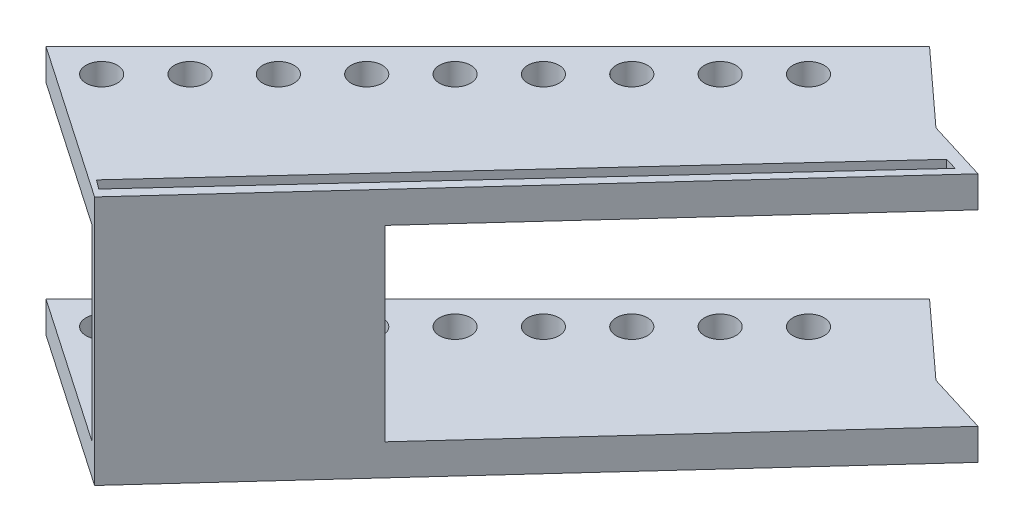
SolidWorks part; units mm, degrees
material "Chrome Stainless Steel"
ref_plane "Front Plane" through (0, 0, 0) normal (0, 0, 1) x (1, 0, 0)
ref_plane "Top Plane" through (0, 0, 0) normal (0, 1, 0) x (1, 0, 0)
ref_plane "Right Plane" through (0, 0, 0) normal (1, 0, 0) x (0, 0, -1)
sketch "Sketch1" plane through (0, 0, 0) normal (0, 1, 0) x (1, 0, 0)
  line L0 (0, 0) -> (179.6051, 179.6051)
  line L1 (179.6051, 179.6051) -> (209.5356, 152.2723)
  line L2 (209.5356, 152.2723) -> (234.2755, 144.6303)
  line L3 (234.2755, 144.6303) -> (62.8444, -43.0932)
  line L4 (62.8444, -43.0932) -> (0, 0)
  dimension "D1" = 254
  dimension "D2" = 76.2
extrude "Boss-Extrude1" add sketch "Sketch1" along normal blind 101.6
ref_plane "Plane1" through (0, 0, 0) normal (-0.7071, 0, -0.7071) x (-0.7071, 0, 0.7071)
sketch "Sketch2" plane through (0, 0, 0) normal (-0.7071, 0, -0.7071) x (-0.7071, 0, 0.7071)
  line L0 (-267.9269, 88.9) -> (0, 88.9)
  line L1 (-267.9269, 101.6) -> (-267.9269, 0) construction
  line L2 (0, 101.6) -> (0, 0) construction
  line L3 (0, 88.9) -> (0, 12.7)
  line L4 (0, 12.7) -> (-267.9269, 12.7)
  line L5 (-267.9269, 12.7) -> (-267.9269, 88.9)
  line L6 (-254, 101.6) -> (0, 101.6) construction
  dimension "D1" = 76.2
  dimension "D2" = 12.7
extrude "Cut-Extrude1" cut sketch "Sketch2" against normal blind 71.12
ref_plane "Plane2" through (0, 101.6, 0) normal (0, 1, 0) x (1, 0, 0)
sketch "Sketch3" plane through (0, 101.6, 0) normal (0, 1, 0) x (1, 0, 0)
  line L4 (179.6051, 179.6051) -> (0, 0) construction
  circle A0 centre (21.0725, 1.5529) radius 6.35
  circle A1 centre (39.033, 19.5135) radius 6.35
  circle A2 centre (56.9935, 37.474) radius 6.35
  circle A3 centre (74.9541, 55.4345) radius 6.35
  circle A4 centre (92.9146, 73.395) radius 6.35
  circle A5 centre (110.8751, 91.3555) radius 6.35
  circle A6 centre (128.8356, 109.316) radius 6.35
  circle A7 centre (146.7961, 127.2765) radius 6.35
  circle A8 centre (164.7566, 145.237) radius 6.35
  dimension "D1" = 12.7
  dimension "D3" = 13.8024
  dimension "D2" = 9
extrude "Cut-Extrude3" cut sketch "Sketch3" against normal through all
sketch "Sketch4" plane through (0, 101.6, 0) normal (0, 1, 0) x (1, 0, 0)
  line L0 (57.221, -36.7013) -> (222.7462, 143.3134)
  line L1 (222.7462, 143.3134) -> (227.727, 141.9407)
  line L2 (227.727, 141.9407) -> (60.9242, -39.4635)
  line L3 (60.9242, -39.4635) -> (57.221, -36.7013)
extrude "Cut-Extrude4" cut sketch "Sketch4" against normal blind 7.62
ref_plane "Plane3" through (0, 0, 0) normal (0, -1, 0) x (-1, 0, 0)
sketch "Sketch5" plane through (0, 0, 0) normal (0, -1, 0) x (-1, 0, 0)
  line L0 (-218.9133, 144.7425) -> (-62.8568, -25.3762)
  line L1 (-62.8568, -25.3762) -> (-58.0715, -30.5927)
  line L2 (-58.0715, -30.5927) -> (-62.8568, -34.9825)
  line L3 (-62.8568, -34.9825) -> (-227.7255, 144.7425)
  line L4 (-227.7255, 144.7425) -> (-218.9133, 144.7425)
extrude "Cut-Extrude5" cut sketch "Sketch5" against normal blind 7.62
